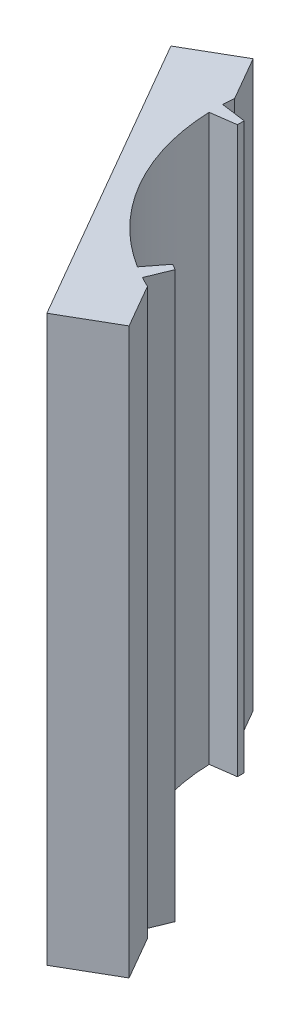
SolidWorks part; units mm, degrees
ref_plane "Front Plane" through (0, 0, 0) normal (0, 0, 1) x (1, 0, 0)
ref_plane "Top Plane" through (0, 0, 0) normal (0, 1, 0) x (1, 0, 0)
ref_plane "Right Plane" through (0, 0, 0) normal (1, 0, 0) x (0, 0, -1)
sketch "Sketch1" plane through (0, 0, 0) normal (0, 1, 0) x (1, 0, 0)
  line L1 (-14.4004, 0) -> (-27.5057, 0) construction
  line L2 (-16.1883, 0.3) -> (-18.3976, 0.3)
  line L3 (-16.1883, -0.3) -> (-18.3976, -0.3)
  line L7 (-16.1883, 0.3) -> (-18.3902, 0.6)
  line L8 (-16.1883, -0.3) -> (-18.3902, -0.6)
  line L9 (0, 0) -> (-32.8396, 0) construction
  line L10 (0, 0) -> (-16.4364, -28.4687) construction
  line L11 (-16.1883, 0.3) -> (-16.1883, -0.3)
  line L12 (0, 0) -> (-15.9349, -9.2) construction
  line L13 (-7.8343, -14.1694) -> (-8.3539, -13.8694)
  line L14 (-7.8343, -14.1694) -> (-8.6755, -16.2264)
  line L15 (-8.3539, -13.8694) -> (-9.7147, -15.6264)
  line L16 (-10.1669, -23.1904) -> (-25.1669, 2.7904)
  line L17 (-25.1669, 2.7904) -> (-20.553, 5.4542)
  line L18 (-20.553, 5.4542) -> (-5.553, -20.5265)
  line L19 (-5.553, -20.5265) -> (-10.1669, -23.1904)
  line L20 (-20.6488, 5.6202) -> (-5.4572, -20.6925) construction
  line L21 (-15.9349, -9.2) -> (-12.6631, -14.8669) construction
  circle A0 centre (0, 0) radius 18.4
  circle A1 centre (0, 0) radius 21.4
  dimension "D1" = 36.8
  dimension "D3" = 0.6
  dimension "D4" = 1.2
  dimension "D5" = 60
  dimension "D6" = 30
  dimension "D7" = 30
  dimension "D8" = 2
  dimension "D2" = 3
extrude "Boss-Extrude1" add sketch "Sketch1" along normal blind 50 contours A1 L16 L19 | L17 A1 L16 L19 L18 A0 | L15 A0 L14 L18 | L15 L18 L14 L13 | L3 A0 L8 L18 | L2 A0 L3 L18 | L7 A0 L2 L18 | L7 L18 L2 | L2 L18 L3 L11 | L3 L18 L8 | A1 L17 L16
